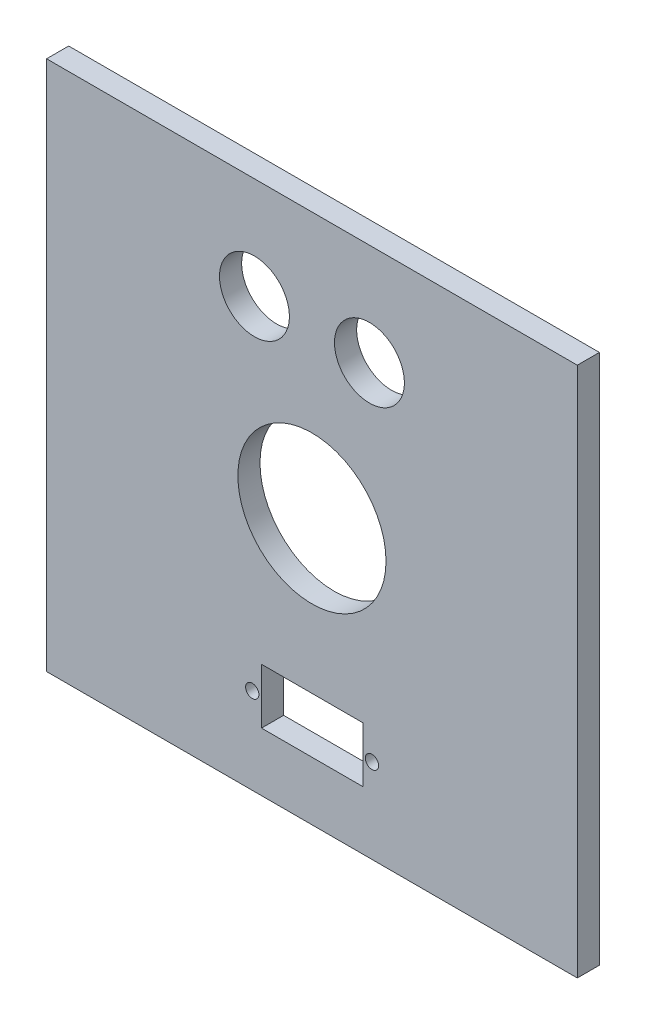
SolidWorks part; units mm, degrees
ref_plane "Plano frontal" through (0, 0, 0) normal (0, 0, 1) x (1, 0, 0)
ref_plane "Plano superior" through (0, 0, 0) normal (0, 1, 0) x (1, 0, 0)
ref_plane "Plano direito" through (0, 0, 0) normal (1, 0, 0) x (0, 0, -1)
sketch "Esboço1" plane through (0, 0, 0) normal (0, 0, 1) x (1, 0, 0)
  line L1 (0, 0) -> (120, 0)
  line L2 (0, 0) -> (0, 120)
  line L3 (0, 120) -> (120, 120)
  line L4 (120, 0) -> (120, 120)
  dimension "D1" = 120
  dimension "D2" = 120
extrude "Ressalto-extrusão1" add sketch "Esboço1" along normal blind 5
sketch "Esboço2" plane through (0, 0, 5) normal (0, 0, 1) x (1, 0, 0)
  line L0 (0, 120) -> (120, 0) construction
  line L1 (120, 0) -> (120, 120) construction
  line L2 (120, 120) -> (0, 0) construction
  circle A0 centre (60, 60) radius 16.75
  dimension "D1" = 33.5
extrude "Corte-extrusão1" cut sketch "Esboço2" against normal blind 13
sketch "Esboço3" plane through (0, 0, 0) normal (0, 0, 1) x (1, 0, 0)
  line L0 (47.903, 25.7337) -> (44.4, 25.7337) construction
  line L1 (48.6, 25.6231) -> (44.4, 25.7337) construction
  line L2 (71.742, 25.0136) -> (71.5, 25.02) construction
  line L3 (0, 120) -> (0, 0) construction
  line L4 (0, 13.2338) -> (11.5867, 16.2139) construction
  line L5 (120, 0) -> (120, 120) construction
  line L6 (0, 16.2139) -> (11.5867, 16.2139) construction
  line L7 (0, 0) -> (0, 43.25) construction
  line L9 (120, 0) -> (120, 21.625) construction
  line L12 (48.6, 25.7337) -> (71.5, 25.7338)
  line L13 (48.6, 25.7337) -> (48.6, 13.2337)
  line L14 (48.6, 13.2337) -> (71.5, 13.2337)
  line L15 (71.5, 25.7338) -> (71.5, 13.2337)
  line L19 (75.7, 24.9093) -> (75.2868, 24.9202) construction
  line L22 (46.4907, 19.4562) -> (46.5, 19.4838) construction
  line L23 (75.7, 24.9093) -> (75.3082, 24.9863) construction
  line L24 (46.4907, 19.4562) -> (46.5093, 19.456) construction
  line L25 (71.5, 25.7338) -> (71.742, 25.0136) construction
  line L27 (75.7, 26.1955) -> (75.2868, 24.9202) construction
  line L28 (48.5632, 25.6241) -> (48.6, 25.7337) construction
  line L29 (48.2099, 25.6334) -> (48.6, 25.7337) construction
  line L30 (46.5, 19.4838) -> (46.5093, 19.456) construction
  circle A1 centre (46.5, 19.4838) radius 1.5
  circle A2 centre (73.5666, 19.0996) radius 1.5
  dimension "D5" = 3
  dimension "D6" = 3
  dimension "D1" = 22.9
  dimension "D3" = 12.5
extrude "Corte-extrusão2" cut sketch "Esboço3" along normal blind 28 and the other way blind 29
sketch "Esboço4" plane through (0, 0, 0) normal (0, 0, 1) x (1, 0, 0)
  line L0 (60, 73.95) -> (0, 73.95) construction
  line L1 (0, 120) -> (0, 0) construction
  line L2 (0, 73.95) -> (120, 73.95) construction
  line L3 (120, 0) -> (120, 120) construction
  line L4 (120, 73.95) -> (120, 120) construction
  line L5 (120, 120) -> (0, 120) construction
  circle A0 centre (47, 96.975) radius 7.9
  circle A1 centre (73, 96.975) radius 7.9
  dimension "D1" = 15.8
  dimension "D2" = 15.8
  dimension "D3" = 26
  dimension "D4" = 13
extrude "Corte-extrusão3" cut sketch "Esboço4" along normal blind 32 and the other way blind 28
